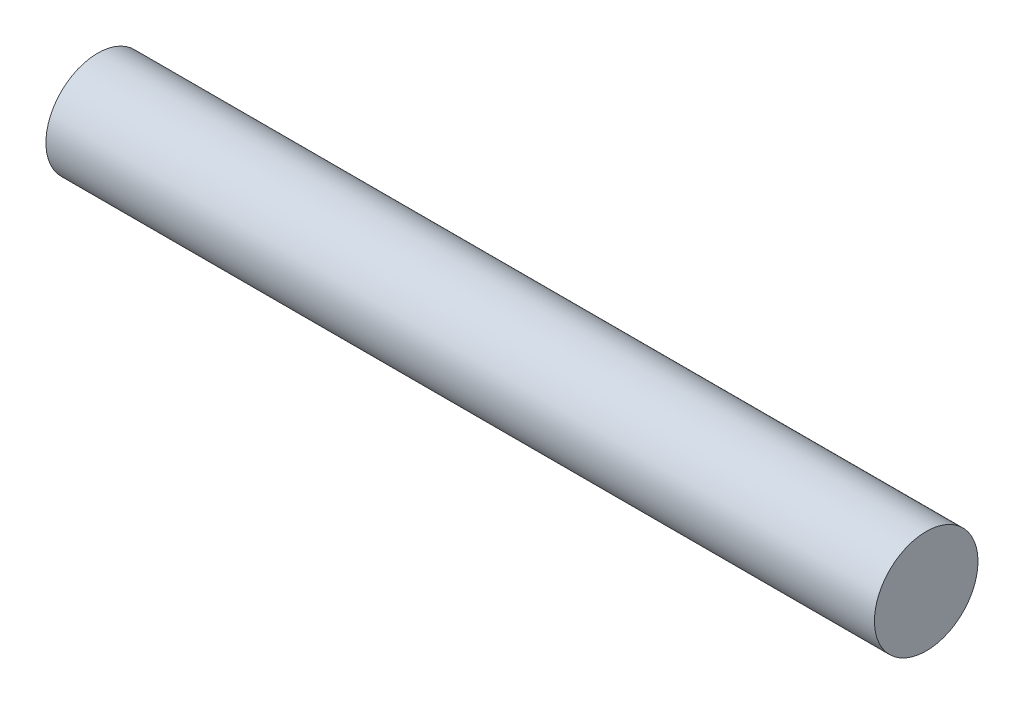
SolidWorks part; units mm, degrees
material "Titanium Ti-5Al-2.5Sn"
ref_plane "Front Plane" through (0, 0, 0) normal (0, 0, 1) x (1, 0, 0)
ref_plane "Top Plane" through (0, 0, 0) normal (0, 1, 0) x (1, 0, 0)
ref_plane "Right Plane" through (0, 0, 0) normal (1, 0, 0) x (0, 0, -1)
sketch "Sketch1" plane through (0, 0, 0) normal (1, 0, 0) x (0, 0, -1)
  circle A0 centre (0, 0) radius 1.5875
extrude "Boss-Extrude1" add sketch "Sketch1" along normal blind 25.4
